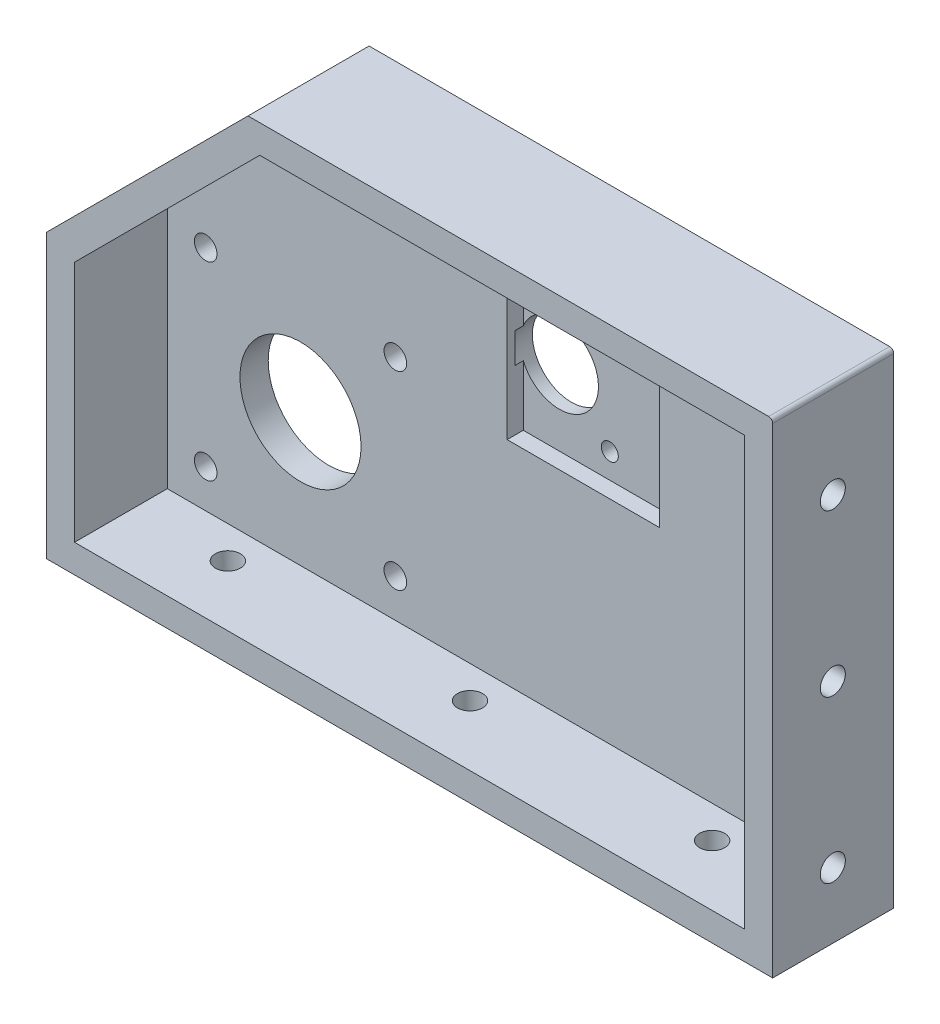
SolidWorks part; units mm, degrees
material "ABS"
ref_plane "Front Plane" through (0, 0, 0) normal (0, 0, 1) x (1, 0, 0)
ref_plane "Top Plane" through (0, 0, 0) normal (0, 1, 0) x (1, 0, 0)
ref_plane "Right Plane" through (0, 0, 0) normal (1, 0, 0) x (0, 0, -1)
sketch "Sketch1" plane through (0, 0, 0) normal (0, 0, 1) x (1, 0, 0)
  line L0 (-48.5799, 70.7779) -> (-98.5799, 20.7779)
  line L1 (-48.5799, 70.7779) -> (80.4201, 70.7779)
  line L2 (-98.5799, 20.7779) -> (-98.5799, -49.2221)
  line L3 (-98.5799, -49.2221) -> (81.4201, -49.2221)
  line L4 (81.4201, 69.7779) -> (81.4201, -49.2221)
  arc A0 (80.4201, 70.7779) -> (81.4201, 69.7779) centre (80.4201, 69.7779) cw
  point P6 (81.4201, 70.7779)
  point P8 (-98.5799, 70.7779)
  point P9 (-98.5799, 70.7779)
  dimension "D3" = 1
  dimension "D1" = 180
  dimension "D2" = 120
extrude "Boss-Extrude1" add sketch "Sketch1" along normal blind 30
shell "Shell1" thickness 7
sketch "Sketch2" plane through (0, 0, 7) normal (0, 0, 1) x (1, 0, 0)
  line L0 (80.4201, 70.7779) -> (-48.5799, 70.7779) construction
  line L1 (-98.5799, 20.7779) -> (-98.5799, -49.2221) construction
  circle A0 centre (-58.5799, -9.2221) radius 15
  dimension "D1" = 80
  dimension "D2" = 40
extrude "Cut-Extrude1" cut sketch "Sketch2" against normal blind 20
sketch "Sketch3" plane through (0, 0, 7) normal (0, 0, 1) x (1, 0, 0)
  circle A0 centre (-82.0799, 14.2779) radius 2.806
  circle A1 centre (-58.5799, -9.2221) radius 15 construction
  dimension "D1" = 23.5
  dimension "D2" = 23.5
extrude "Cut-Extrude2" cut sketch "Sketch3" against normal blind 20
pattern_linear "LPattern1" count 2 spacing 47 along (1, 0, 0) count 2 spacing 47 along (0, -1, 0) of "Cut-Extrude2"
sketch "Sketch4" plane through (0, 0, 7) normal (0, 0, 1) x (1, 0, 0)
  line L0 (81.4201, -49.2221) -> (81.4201, 69.7779) construction
  line L1 (-7.3787, 48.7779) -> (30.4201, 48.7779)
  line L2 (-7.3787, 48.7779) -> (-7.3787, 10.4125)
  line L3 (-7.3787, 10.4125) -> (30.4201, 10.4125)
  line L4 (30.4201, 48.7779) -> (30.4201, 10.4125)
  line L5 (80.4201, 70.7779) -> (-48.5799, 70.7779) construction
  dimension "D1" = 51
  dimension "D2" = 22
extrude "Cut-Extrude3" cut sketch "Sketch4" against normal blind 4
sketch "Sketch5" plane through (0, 0, 5) normal (0, 0, -1) x (-1, 0, 0)
  circle A0 centre (-1.5594, 29.0878) radius 9.6894
extrude "Cut-Extrude4" cut sketch "Sketch5" along normal blind 10
sketch "Sketch6" plane through (0, 0, 5) normal (0, 0, -1) x (-1, 0, 0)
  circle A0 centre (-14.0594, 41.5878) radius 2.1094
  circle A1 centre (-1.5594, 29.0878) radius 9.6894 construction
  dimension "D1" = 12.5
  dimension "D2" = 12.5
extrude "Cut-Extrude5" cut sketch "Sketch6" along normal blind 10
pattern_linear "LPattern2" count 2 spacing 25 along (-1, 0, 0) count 2 spacing 25 along (0, -1, 0) of "Cut-Extrude5"
sketch "Sketch7" plane through (0, -49.2221, 0) normal (0, -1, 0) x (1, 0, 0)
  line L0 (-98.5799, 30) -> (81.4201, 30) construction
  line L1 (-98.5799, 30) -> (-98.5799, 0) construction
  circle A0 centre (-68.5799, 15) radius 3.1
  dimension "D1" = 15
  dimension "D2" = 30
extrude "Cut-Extrude6" cut sketch "Sketch7" against normal blind 10
pattern_linear "LPattern3" count 3 spacing 60 along (1, 0, 0) of "Cut-Extrude6"
sketch "Sketch8" plane through (81.4201, 0, 0) normal (1, 0, 0) x (0, 0, -1)
  circle A0 centre (-15.099, -32.9745) radius 3.1067
extrude "Cut-Extrude7" cut sketch "Sketch8" against normal blind 10
pattern_linear "LPattern4" count 3 spacing 40 along (0, 1, 0) of "Cut-Extrude7"
